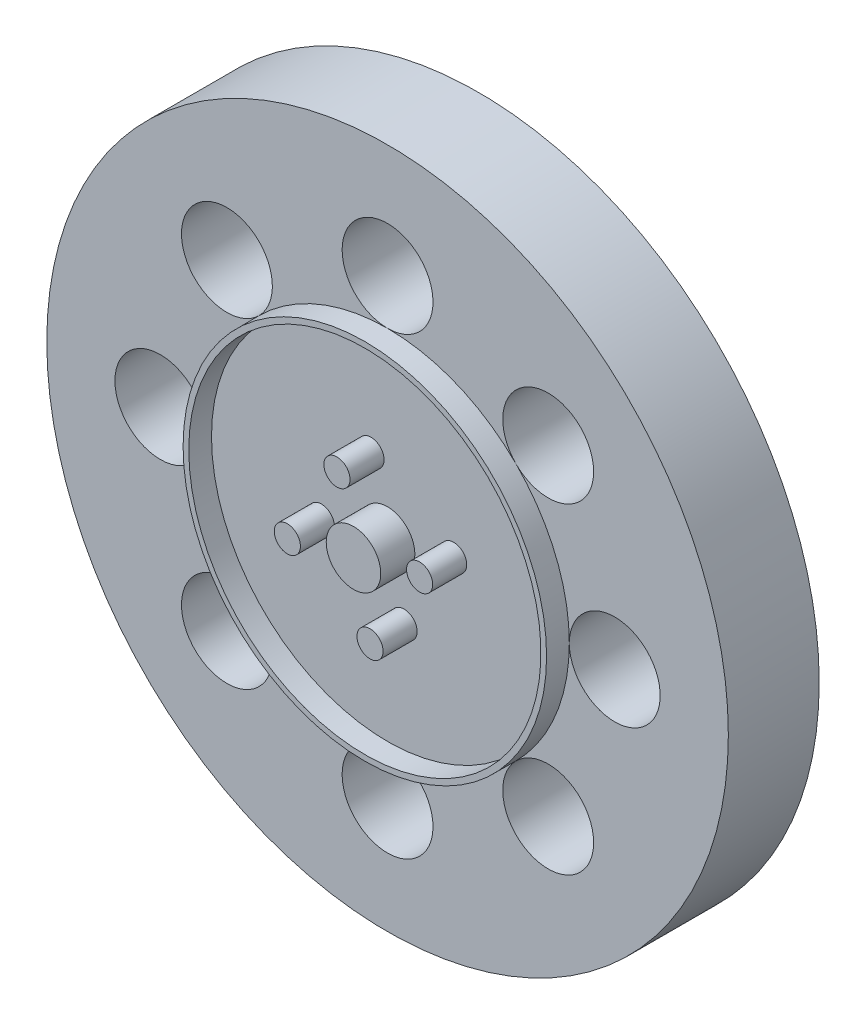
SolidWorks part; units mm, degrees
ref_plane "前视基准面" through (0, 0, 0) normal (0, 0, 1) x (1, 0, 0)
ref_plane "上视基准面" through (0, 0, 0) normal (0, 1, 0) x (1, 0, 0)
ref_plane "右视基准面" through (0, 0, 0) normal (1, 0, 0) x (0, 0, -1)
sketch "草图2" plane through (0, 0, -10) normal (0, 0, -1) x (-1, 0, 0)
  circle A0 centre (0, 0) radius 2.4
  dimension "D1" = 4.8
extrude "凸台-拉伸1" add sketch "草图2" against normal blind 3 contours A0
sketch "草图3" plane through (0, 0, -10) normal (0, 0, -1) x (-1, 0, 0)
  circle A0 centre (0, 0) radius 30
  circle A1 centre (-5.8209, 1.455) radius 1.25 construction
  circle A2 centre (-1.455, -5.8209) radius 1.25 construction
  circle A3 centre (5.8209, -1.455) radius 1.25 construction
  circle A4 centre (1.455, 5.8209) radius 1.25 construction
  circle A5 centre (-5.8209, 1.455) radius 1.25
  circle A6 centre (-1.455, -5.8209) radius 1.25
  circle A7 centre (5.8209, -1.455) radius 1.25
  circle A8 centre (1.455, 5.8209) radius 1.25
  circle A9 centre (5.8209, -1.455) radius 1.15
  circle A10 centre (-1.455, -5.8209) radius 1.15
  circle A11 centre (-5.8209, 1.455) radius 1.15
  circle A12 centre (1.455, 5.8209) radius 1.15
  point P16 (5.8209, -1.455)
  point P17 (1.455, 5.8209)
  point P18 (-5.8209, 1.455)
  point P19 (-1.455, -5.8209)
  dimension "D1" = 60
  dimension "D2" = 2.3
  dimension "D3" = 2.3
  dimension "D4" = 2.3
  dimension "D5" = 2.3
extrude "凸台-拉伸2" add sketch "草图3" against normal blind 3 separate body contours A9 | A10 | A11 | A12
sketch "草图4" plane through (0, 0, -10) normal (0, 0, -1) x (-1, 0, 0)
  circle A0 centre (0, 0) radius 15.5
  circle A1 centre (0, 0) radius 16
  dimension "D1" = 31
  dimension "D2" = 32
extrude "凸台-拉伸3" add sketch "草图4" against normal blind 2 separate body contours A1 | A0
sketch "草图5" plane through (0, 0, -10) normal (0, 0, -1) x (-1, 0, 0)
  circle A0 centre (0, 0) radius 30
  dimension "D1" = 60
extrude "凸台-拉伸4" add sketch "草图5" along normal blind 8 contours A0
sketch "草图6" plane through (0, 0, -18) normal (0, 0, -1) x (-1, 0, 0)
  line L0 (0, 30) -> (0, -30) construction
  circle A0 centre (0, -20) radius 4
  circle A1 centre (-14.1421, -14.1421) radius 4
  circle A2 centre (-20, 0) radius 4
  circle A3 centre (-14.1421, 14.1421) radius 4
  circle A4 centre (0, 20) radius 4
  circle A5 centre (14.1421, 14.1421) radius 4
  circle A6 centre (20, 0) radius 4
  circle A7 centre (14.1421, -14.1421) radius 4
  circle A8 centre (0, 0) radius 30 construction
  point P18 (0, 0)
  point P22 (0, 0)
  dimension "D1" = 8
  dimension "D2" = 20
extrude "切除-拉伸1" cut sketch "草图6" against normal up to next
sketch "草图7" plane through (0, 0, -18) normal (0, 0, -1) x (-1, 0, 0)
  line L0 (-30, 0) -> (30, 0) construction
  circle A0 centre (12, 0) radius 1
  circle A1 centre (0, 12) radius 1
  circle A2 centre (-12, 0) radius 1
  circle A3 centre (0, -12) radius 1
  circle A4 centre (0, 0) radius 30 construction
  point P11 (0, 0)
  dimension "D1" = 2
  dimension "D2" = 12
extrude "切除-拉伸2" cut sketch "草图7" against normal blind 4
sketch "草图9" plane through (0, 0, -18) normal (0, 0, -1) x (-1, 0, 0)
  line L0 (0, 0) -> (-12, 0) construction
  line L1 (0, 0) -> (0, 12) construction
  line L2 (-15.5, -0.3) -> (-15.5, 0.3)
  line L3 (-15.5, 0.3) -> (-14.5, 0.3)
  line L4 (-14.5, 0.3) -> (-14.5, -0.3)
  line L5 (-15.5, -0.3) -> (-14.5, -0.3)
  point P12 (-14.5, 0)
  point P14 (-15.5, 0)
  dimension "D1" = 1
  dimension "D2" = 0.3
  dimension "D3" = 14.5
extrude "切除-拉伸3" cut sketch "草图9" against normal blind 1
